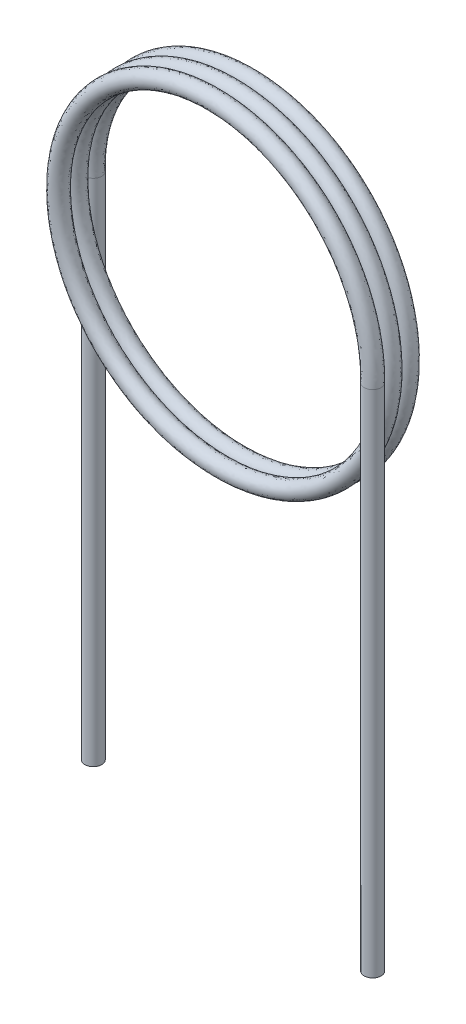
SolidWorks part; units mm, degrees
ref_plane "Piano frontale" through (0, 0, 0) normal (0, 0, 1) x (1, 0, 0)
ref_plane "Piano superiore" through (0, 0, 0) normal (0, 1, 0) x (1, 0, 0)
ref_plane "Piano destro" through (0, 0, 0) normal (1, 0, 0) x (0, 0, -1)
sketch "Schizzo1" plane through (0, 0, 0) normal (0, 0, 1) x (1, 0, 0)
  circle A0 centre (0, 0) radius 4.75
  dimension "D1" = 9.5
curve "Elica/Spirale1" pitch 0.51 height 1.275 turns 2.5
sketch "Schizzo2" plane through (0, 0, 0) normal (0, 1, 0) x (1, 0, 0)
  line L0 (-4.75, 0) -> (0, 0) construction
  circle A0 centre (-4.75, 0) radius 0.25
  spline S0 degree 3 poles (-4.75, 0) (-4.75, -0.0106) (-4.5027, -0.0319) (-3.4462, -0.0637) (-1.338, -0.1063) (1.338, -0.1488) (3.4462, -0.1912) (4.5027, -0.2231) (4.8737, -0.255) (4.5027, -0.2869) (3.4462, -0.3187) (1.338, -0.3613) (-1.338, -0.4038) (-3.4462, -0.4462) (-4.5027, -0.4781) (-4.8737, -0.51) (-4.5027, -0.5419) (-3.4462, -0.5737) (-1.338, -0.6163) (1.338, -0.6587) (3.4462, -0.7013) (4.5027, -0.7331) (4.8737, -0.765) (4.5027, -0.7969) (3.4462, -0.8288) (1.338, -0.8712) (-1.338, -0.9137) (-3.4462, -0.9563) (-4.5027, -0.9881) (-4.8737, -1.02) (-4.5027, -1.0519) (-3.4462, -1.0838) (-1.338, -1.1262) (1.338, -1.1687) (3.4462, -1.2113) (4.5027, -1.2431) (4.75, -1.2644) (4.75, -1.275) knots 0 0 0 0 0.025 0.05 0.075 0.125 0.15 0.175 0.2 0.225 0.25 0.275 0.325 0.35 0.375 0.4 0.425 0.45 0.475 0.525 0.55 0.575 0.6 0.625 0.65 0.675 0.725 0.75 0.775 0.8 0.825 0.85 0.875 0.925 0.95 0.975 1 1 1 1 construction
  dimension "D1" = 0.5
sweep "Sweep1" add profiles "Schizzo2" path "Elica/Spirale1"
sketch "Schizzo3" plane through (0, 0, 0) normal (0, 1, 0) x (1, 0, 0)
  circle A0 centre (4.75, -1.275) radius 0.25
  circle A1 centre (-4.75, 0) radius 0.25
  circle A2 centre (4.75, -1.275) radius 0.25 construction
  circle A3 centre (-4.75, 0) radius 0.25 construction
  spline S0 degree 3 poles (-4.75, 0) (-4.75, -0.0106) (-4.5027, -0.0319) (-3.4462, -0.0637) (-1.338, -0.1063) (1.338, -0.1488) (3.4462, -0.1912) (4.5027, -0.2231) (4.8737, -0.255) (4.5027, -0.2869) (3.4462, -0.3187) (1.338, -0.3613) (-1.338, -0.4038) (-3.4462, -0.4462) (-4.5027, -0.4781) (-4.8737, -0.51) (-4.5027, -0.5419) (-3.4462, -0.5737) (-1.338, -0.6163) (1.338, -0.6587) (3.4462, -0.7013) (4.5027, -0.7331) (4.8737, -0.765) (4.5027, -0.7969) (3.4462, -0.8288) (1.338, -0.8712) (-1.338, -0.9137) (-3.4462, -0.9563) (-4.5027, -0.9881) (-4.8737, -1.02) (-4.5027, -1.0519) (-3.4462, -1.0838) (-1.338, -1.1262) (1.338, -1.1687) (3.4462, -1.2113) (4.5027, -1.2431) (4.75, -1.2644) (4.75, -1.275) knots 0 0 0 0 0.025 0.05 0.075 0.125 0.15 0.175 0.2 0.225 0.25 0.275 0.325 0.35 0.375 0.4 0.425 0.45 0.475 0.525 0.55 0.575 0.6 0.625 0.65 0.675 0.725 0.75 0.775 0.8 0.825 0.85 0.875 0.925 0.95 0.975 1 1 1 1 construction
extrude "Estrusione-Estrusione1" add sketch "Schizzo3" against normal blind 15
